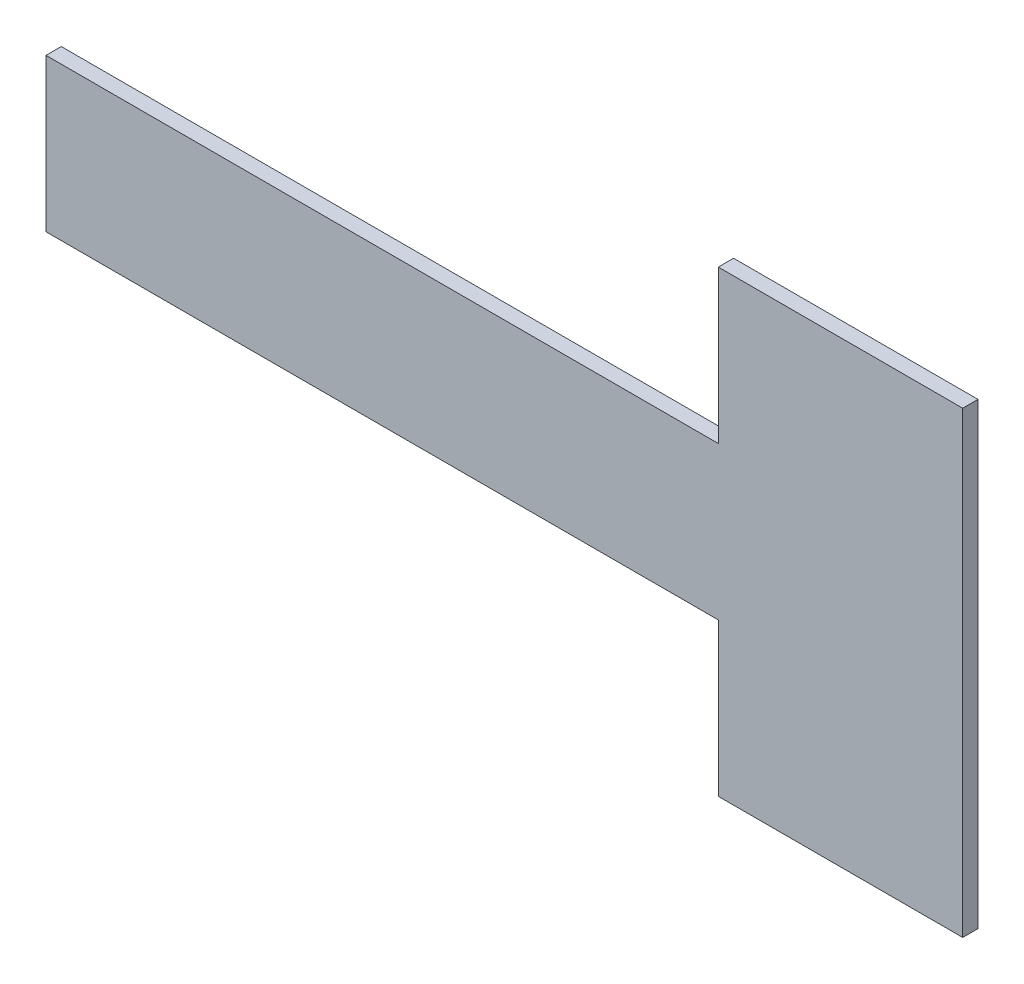
SolidWorks part; units mm, degrees
ref_plane "Front Plane" through (0, 0, 0) normal (0, 0, 1) x (1, 0, 0)
ref_plane "Top Plane" through (0, 0, 0) normal (0, 1, 0) x (1, 0, 0)
ref_plane "Right Plane" through (0, 0, 0) normal (1, 0, 0) x (0, 0, -1)
sketch "Sketch1" plane through (0, 0, 0) normal (0, 0, 1) x (1, 0, 0)
  line L1 (0, 0) -> (76.2, 0)
  line L2 (0, 0) -> (0, -12.7)
  line L3 (0, -12.7) -> (76.2, -12.7)
  line L4 (76.2, 0) -> (76.2, -12.7)
  dimension "D1" = 12.7
  dimension "D2" = 76.2
extrude "Boss-Extrude1" add sketch "Sketch1" along normal blind 1.27
sketch "Sketch2" plane through (0, 0, 0) normal (0, 0, -1) x (-1, 0, 0)
  line L0 (-76.2, -12.7) -> (-76.2, -25.4)
  line L1 (0, -12.7) -> (-76.2, -12.7) construction
  line L2 (-76.2, -25.4) -> (-55.88, -25.4)
  line L3 (-55.88, -25.4) -> (-55.88, -12.7)
  line L4 (-76.2, 0) -> (-76.2, 12.7)
  line L5 (-76.2, 12.7) -> (-55.88, 12.7)
  line L6 (-55.88, 12.7) -> (-55.88, 0)
  line L7 (-76.2, 0) -> (0, 0) construction
  line L8 (-55.88, -12.7) -> (-76.594, -12.7)
  line L9 (-76.2, 0) -> (-55.88, 0)
  line M8 (0, 0) -> (-76.2, 0)
  line M10 (-76.2, -12.7) -> (0, -12.7)
  dimension "D1" = 20.32
  dimension "D2" = 12.7
  dimension "D3" = 12.7
  dimension "D4" = 12.7
  dimension "D5" = 12.7
  dimension "D6" = 20.32
extrude "Boss-Extrude4" add sketch "Sketch2" against normal blind 1.27 contours L6 L5 L4 M8 | L2 L3 L0 M10
